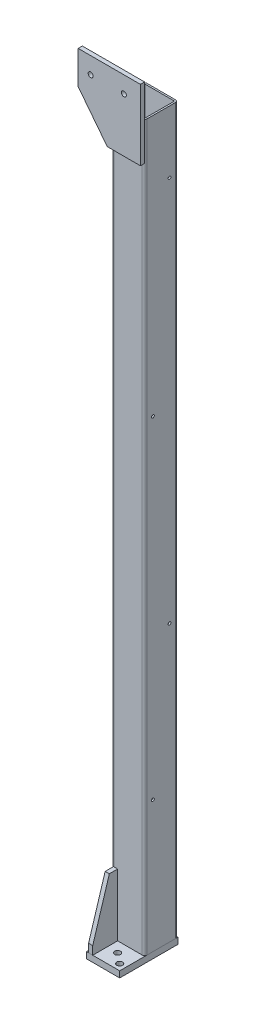
SolidWorks part; units mm, degrees
ref_plane "前视基准面" through (0, 0, 0) normal (0, 0, 1) x (1, 0, 0)
ref_plane "上视基准面" through (0, 0, 0) normal (0, 1, 0) x (1, 0, 0)
ref_plane "右视基准面" through (0, 0, 0) normal (1, 0, 0) x (0, 0, -1)
other "Q235A"
sketch "草图1" plane through (0, 0, 0) normal (0, 0, 1) x (1, 0, 0)
  line L0 (0, 1745) -> (0, 0)
  dimension "D2" = 1745
other "结构构件1"
ref_plane "基准面1" through (0, 1745, 0) normal (0, -1, 0) x (0, 0, 1)
sketch "Sketch11" plane through (0, 1745, 0) normal (0, -1, 0) x (0, 0, 1)
  line L0 (-34, -36) -> (34, -36)
  line L1 (-36, -34) -> (-36, 34)
  line L2 (34, 36) -> (-34, 36)
  line L3 (36, 34) -> (36, -34)
  line L4 (-34, -40) -> (34, -40)
  line L5 (-40, -34) -> (-40, 34)
  line L6 (34, 40) -> (-34, 40)
  line L7 (40, 34) -> (40, -34)
  arc A0 (40, 34) -> (34, 40) centre (34, 34) ccw
  arc A1 (34, -40) -> (40, -34) centre (34, -34) ccw
  arc A2 (-40, -34) -> (-34, -40) centre (-34, -34) ccw
  arc A3 (-34, 40) -> (-40, 34) centre (-34, 34) ccw
  arc A4 (-34, 36) -> (-36, 34) centre (-34, 34) ccw
  arc A5 (36, 34) -> (34, 36) centre (34, 34) ccw
  arc A6 (34, -36) -> (36, -34) centre (34, -34) ccw
  arc A7 (-36, -34) -> (-34, -36) centre (-34, -34) ccw
  point P0 (-40, 0)
  point P1 (40, 0)
  point P2 (0, 40)
  point P3 (0, -40)
  point P4 (0, 0)
  point P5 (-40, -40)
  point P6 (40, -40)
  point P7 (40, 40)
  point P8 (-40, 40)
  point P33 (0, 0)
  dimension "D1" = 6
  dimension "Thickness" = 4
  dimension "V_leg" = 80
sketch "草图4" plane through (0, 0, 0) normal (0, -1, 0) x (1, 0, 0)
  line L0 (-34, -40) -> (34, -40) construction
  line L1 (40, -34) -> (40, 34) construction
  line L5 (-40, 100) -> (40, 100)
  line L6 (-40, 100) -> (-40, -40)
  line L7 (-40, -40) -> (40, -40)
  line L8 (40, 100) -> (40, -40)
  dimension "D1" = 80
  dimension "D2" = 140
extrude "凸台-拉伸1" add sketch "草图4" along normal blind 15 separate body
hole_wizard "Ø14.0 (14) 直径孔1" positions "草图13" profile "草图12" hole size "Ø14.0" standard "GB"
sketch "草图13" plane through (0, 0, 0) normal (0, 1, 0) x (-1, 0, 0)
  line L0 (-40, 100) -> (40, 100) construction
  line L2 (-40, -40) -> (-40, 100) construction
  point P0 (-25, 85)
  point P1 (0, 65)
  dimension "D1" = 15
  dimension "D2" = 15
  dimension "D3" = 20
  dimension "D4" = 25
sketch "草图12" plane through (25, 0, 85) normal (1, 0, 0) x (0, 0, 1)
  line L0 (0, 0) -> (0, 44.206)
  line L1 (0, 44.206) -> (7, 40)
  line L2 (7, 40) -> (7, 0)
  line L5 (7, 0) -> (0, 0)
  line L10 (0, 44.206) -> (-7, 40) construction
  line L11 (0, -6.35) -> (0, 107.95) construction
  dimension "孔直径" = 14
  dimension "孔深度" = 40
  dimension "导头角度" = 118
ref_plane "基准面2" through (25, 0, 0) normal (1, 0, 0) x (0, 0, -1)
sketch "草图11" plane through (25, 0, 0) normal (1, 0, 0) x (0, 0, -1)
  line L0 (40, 0) -> (-100, 0) construction
  line L1 (-100, 20) -> (-60, 150)
  line L2 (-100, -15) -> (-100, 0) construction
  line L7 (-100, 20) -> (-100, 0)
  line L8 (-100, 0) -> (-40, 0)
  line L9 (-40, 0) -> (-40, 150)
  line L10 (-40, 150) -> (-60, 150)
  dimension "D1" = 20
  dimension "D2" = 150
  dimension "D3" = 20
  dimension "D4" = 60
extrude "凸台-拉伸2" add sketch "草图11" along normal blind 10 from offset 60 separate body
sketch "草图20" plane through (0, 0, 40) normal (0, 0, 1) x (1, 0, 0)
  line L0 (40, 1655) -> (40, 1825)
  line L1 (40, 0) -> (40, 1745) construction
  line L2 (40, 1825) -> (-110, 1825)
  line L3 (-110, 1825) -> (-110, 1745)
  line L4 (-110, 1745) -> (-40, 1655)
  line L5 (-40, 0) -> (-40, 1745) construction
  line L6 (-40, 1655) -> (40, 1655)
  line L7 (34, 1745) -> (-34, 1745) construction
  dimension "D1" = 80
  dimension "D2" = 150
  dimension "D3" = 170
  dimension "D4" = 80
  dimension "D5" = 80
  dimension "D6" = 90
extrude "凸台-拉伸3" add sketch "草图20" along normal blind 10 separate body
hole_wizard "M10 间隙孔1" positions "草图31" profile "草图30" hole size "M10" standard "GB"
sketch "草图31" plane through (0, 0, 40) normal (0, 0, -1) x (-1, 0, 0)
  line L0 (-40, 1825) -> (110, 1825) construction
  line L1 (-40, 1655) -> (-40, 1825) construction
  point P10 (0, 1785)
  point P12 (80, 1785)
  dimension "D1" = 40
  dimension "D2" = 40
  dimension "D3" = 80
sketch "草图30" plane through (0, 1785, 40) normal (1, 0, 0) x (0, 1, 0)
  line L0 (0, 0) -> (0, 33.6052)
  line L1 (0, 33.6052) -> (6, 30)
  line L2 (6, 30) -> (6, 0)
  line L5 (6, 0) -> (0, 0)
  line L10 (0, 33.6052) -> (-6, 30) construction
  line L11 (0, -6.35) -> (0, 107.95) construction
  dimension "孔直径" = 12
  dimension "孔深度" = 30
  dimension "导头角度" = 118
hole_wizard "M8 螺纹孔1" positions "草图33" profile "草图32" tap size "M8" standard "GB"
sketch "草图33" plane through (40, 0, 0) normal (1, 0, 0) x (0, 0, -1)
  line L3 (20, 1585) -> (20, 1605) construction
  line L4 (20, 655) -> (20, 675) construction
  point P17 (20, 1595)
  point P20 (20, 665)
  dimension "D1" = 20
  dimension "D2" = 20
sketch "草图32" plane through (40, 1595, -20) normal (0, 1, 0) x (0, 0, -1)
  line L0 (0, 0) -> (0, 21.7929)
  line L1 (0, 21.7929) -> (3.4, 19.75)
  line L2 (3.4, 19.75) -> (3.4, 0)
  line L5 (3.4, 0) -> (0, 0)
  line L10 (0, 21.7929) -> (-3.4, 19.75) construction
  line L11 (0, -6.35) -> (0, 107.95) construction
  dimension "螺纹孔钻头直径" = 6.8
  dimension "螺纹孔钻头深度" = 19.75
  dimension "导头角度" = 118
cosmetic thread "孔螺蚊线22" parameters "D1"=4, "D2"=8
cosmetic thread "孔螺蚊线26" parameters "D1"=4, "D2"=8
hole_wizard "M8 螺纹孔2" [suppressed] positions "草图35" profile "草图34" tap size "M8" standard "GB"
sketch "草图35" plane through (0, 0, 40) normal (0, 0, 1) x (1, 0, 0)
  line L0 (20, 890) -> (20, 880) construction
  line L2 (20, 590) -> (20, 580) construction
  line L4 (20, 290) -> (20, 280) construction
  point P0 (20, 285)
  point P1 (20, 585)
  point P3 (20, 885)
sketch "草图34" plane through (20, 285, 40) normal (1, 0, 0) x (0, -1, 0)
  line L0 (0, 0) -> (0, 21.7929)
  line L1 (0, 21.7929) -> (3.4, 19.75)
  line L2 (3.4, 19.75) -> (3.4, 0)
  line L5 (3.4, 0) -> (0, 0)
  line L10 (0, 21.7929) -> (-3.4, 19.75) construction
  line L11 (0, -6.35) -> (0, 107.95) construction
  dimension "螺纹孔钻头直径" = 6.8
  dimension "螺纹孔钻头深度" = 19.75
  dimension "导头角度" = 118
cosmetic thread "孔螺蚊线19" [suppressed] parameters "D1"=4, "D2"=8
cosmetic thread "孔螺蚊线20" [suppressed] parameters "D1"=4, "D2"=8
cosmetic thread "孔螺蚊线21" [suppressed] parameters "D1"=4, "D2"=8
hole_wizard "M8 螺纹孔3" positions "草图39" profile "草图38" tap size "M8" standard "GB"
sketch "草图39" plane through (40, 0, 0) normal (1, 0, 0) x (0, 0, -1)
  point P0 (-20, 1117)
  point P3 (-20, 317)
sketch "草图38" plane through (40, 1117, 20) normal (0, 1, 0) x (0, 0, -1)
  line L0 (0, 0) -> (0, 24.2929)
  line L1 (0, 24.2929) -> (3.4, 22.25)
  line L2 (3.4, 22.25) -> (3.4, 0)
  line L5 (3.4, 0) -> (0, 0)
  line L10 (0, 24.2929) -> (-3.4, 22.25) construction
  line L11 (0, -6.35) -> (0, 107.95) construction
  dimension "螺纹孔钻头直径" = 6.8
  dimension "螺纹孔钻头深度" = 22.25
  dimension "导头角度" = 118
cosmetic thread "孔螺蚊线24" parameters "D1"=4, "D2"=8
cosmetic thread "孔螺蚊线25" parameters "D1"=4, "D2"=8
